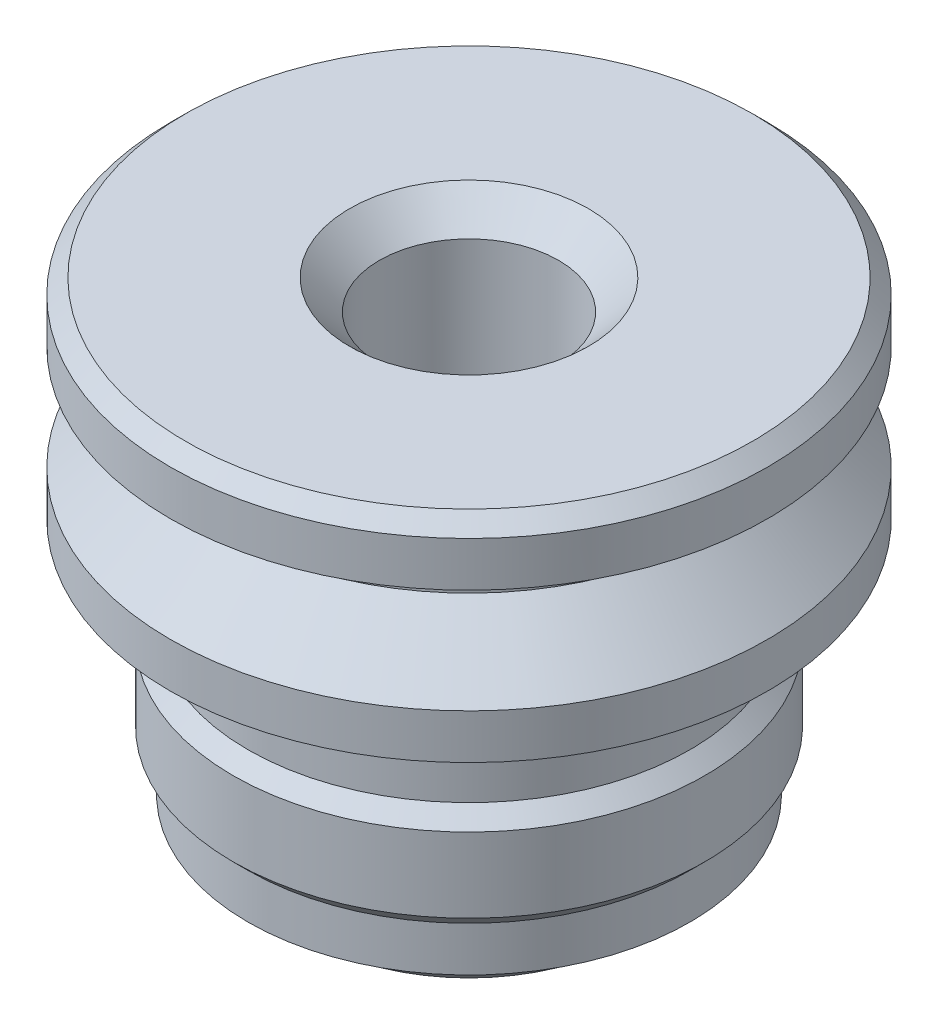
SolidWorks part; units mm, degrees
ref_plane "정면" through (0, 0, 0) normal (0, 0, 1) x (1, 0, 0)
ref_plane "윗면" through (0, 0, 0) normal (0, 1, 0) x (1, 0, 0)
ref_plane "우측면" through (0, 0, 0) normal (1, 0, 0) x (0, 0, -1)
sketch "스케치2" plane through (0, 0, 0) normal (1, 0, 0) x (0, 0, -1)
  line L0 (3, 0) -> (10, 0)
  line L1 (10, 0) -> (10, -2)
  line L2 (10, -2) -> (8, -2)
  line L3 (8, -2) -> (8, -3.5)
  line L4 (8, -3.5) -> (10, -5.5)
  line L5 (10, -5.5) -> (10, -7)
  line L8 (7.9, -13) -> (7.4, -13.5)
  line L9 (7.4, -13.5) -> (7.4, -15)
  line L10 (7.4, -15) -> (5.9, -15)
  line L11 (5.9, -15) -> (5.9, -16.5)
  line L12 (5.9, -16.5) -> (3, -16.5)
  line L13 (3, -16.5) -> (3, 0)
  line L14 (0, 0) -> (0, -16.5) construction
  line L15 (0, -16.5) -> (3, -16.5) construction
  line L16 (3, 0) -> (0, 0) construction
  line L17 (10, -7) -> (7.4, -7)
  line L18 (7.4, -7) -> (7.4, -10)
  line L19 (7.4, -10) -> (7.9, -10.5)
  line L20 (7.9, -10.5) -> (7.9, -13)
  dimension "D1" = 16.5
  dimension "D2" = 1.5
  dimension "D3" = 2
  dimension "D4" = 1.5
  dimension "D5" = 3
  dimension "D6" = 2.5
  dimension "D7" = 1.5
  dimension "D8" = 1.5
  dimension "D9" = 6
  dimension "D10" = 15.8
  dimension "D11" = 20
  dimension "D12" = 2
  dimension "D13" = 135
  dimension "D14" = 1.5
  dimension "D15" = 2
revolve "회전1" add sketch "스케치2" angle 360 about L14
chamfer "모따기1" distance 0.5 angle 45 2 edges at (0, 0, 10) (0, -16.5, 5.9)
chamfer "모따기2" distance 1 angle 45 1 edges at (0, 0, 3)
